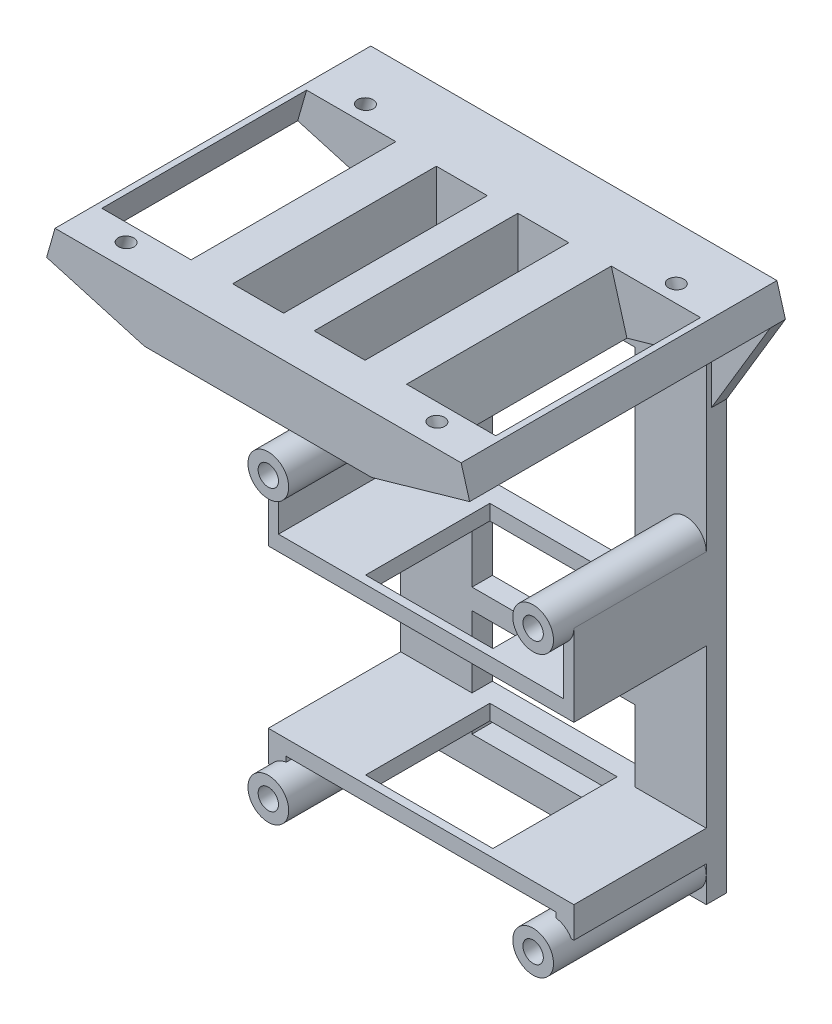
SolidWorks part; units mm, degrees
ref_plane "前基準面" through (0, 0, 0) normal (0, 0, 1) x (1, 0, 0)
ref_plane "上基準面" through (0, 0, 0) normal (0, 1, 0) x (1, 0, 0)
ref_plane "右基準面" through (0, 0, 0) normal (1, 0, 0) x (0, 0, -1)
sketch "草圖1" plane through (0, 0, 0) normal (0, 0, 1) x (1, 0, 0)
  line L0 (-15, 0) -> (15, 0)
  line L1 (-15, 0) -> (-17.2274, 0)
  line L2 (20.7676, -12.3462) -> (15, -14)
  line L3 (15, -14) -> (15, -64)
  line L4 (15, -64) -> (-15, -64)
  line L5 (-15, -64) -> (-15, -14)
  line L6 (-15, -14) -> (-20.7676, -12.3462)
  line L7 (-17.2274, 0) -> (-20.7676, -12.3462)
  line L8 (0, 15.1551) -> (0, -26.7536) construction
  line L9 (15, 0) -> (17.1989, 0)
  line L10 (17.1989, 0) -> (20.7676, -12.3462)
  dimension "D7" = 74
  dimension "D8" = 6
  dimension "D9" = 14
  dimension "D1" = 30
  dimension "D2" = 15
  dimension "D3" = 30
  dimension "D4" = 15
  dimension "D5" = 50
  dimension "D6" = 148
  dimension "D11" = 90
extrude "填料-伸長1" add sketch "草圖1" along normal blind 2
sketch "草圖2" plane through (0, 0, 2) normal (0, 0, 1) x (1, 0, 0)
  line L0 (0, 35.4377) -> (0, -39.094) construction
  line L1 (-19.9407, -9.4624) -> (19.9345, -9.4642)
  line L2 (-20.7676, -12.3462) -> (-11.155, -15.1025)
  line L3 (-11.155, -15.1025) -> (11.155, -15.1025)
  line L4 (11.155, -15.1025) -> (20.7676, -12.3462)
  line L5 (15, -14) -> (20.7676, -12.3462) construction
  line L6 (-20.7676, -12.3462) -> (-15, -14) construction
  line L7 (-20.7676, -12.3462) -> (-19.9407, -9.4624)
  line L8 (-17.2274, 0) -> (-20.7676, -12.3462) construction
  line L12 (20.7676, -12.3462) -> (17.1989, 0) construction
  line L13 (19.9345, -9.4642) -> (20.7676, -12.3462)
  dimension "D1" = 10
  dimension "D2" = 3
  dimension "D3" = 3
extrude "填料-伸長2" add sketch "草圖2" along normal blind 29 and the other way blind 2
sketch "草圖3" plane through (3.5569, -17.2812, 0) normal (-0.2756, 0.9613, 0) x (0.9613, 0.2756, 0)
  line L0 (7.9042, -31) -> (17.9042, -31) construction
  line L5 (17.8978, -6.9) -> (8.8978, -6.9)
  line L6 (17.8978, -6.9) -> (17.8978, -27)
  line L7 (17.8978, -27) -> (8.8978, -27)
  line L8 (8.8978, -6.9) -> (8.8978, -27)
  circle A2 centre (13.3978, -5.2) radius 0.75
  circle A3 centre (13.3978, -28.7) radius 0.75
  dimension "D7" = 1.5
  dimension "D2" = 20.1
  dimension "D3" = 9
  dimension "D4" = 23.5
  dimension "D5" = 1.7
  dimension "D6" = 4
  dimension "D11" = 4.5
extrude "除料-伸長5" cut sketch "草圖3" along normal up to next
sketch "草圖12" plane through (-4.8491, -16.9107, 0) normal (-0.2756, -0.9613, 0) x (0.9613, -0.2756, 0)
  line L0 (-16.56, 31) -> (-16.56, 0) construction
  line L1 (-16.56, 27) -> (-7.56, 27)
  line L2 (-16.56, 27) -> (-16.56, 6.9)
  line L3 (-16.56, 6.9) -> (-7.56, 6.9)
  line L4 (-7.56, 27) -> (-7.56, 6.9)
  line L5 (-16.56, 31) -> (-6.56, 31) construction
  circle A0 centre (-12.06, 28.7) radius 0.75
  circle A1 centre (-12.06, 5.2) radius 0.75
  dimension "D7" = 1.5
  dimension "D8" = 1.5
  dimension "D1" = 9
  dimension "D2" = 20.1
  dimension "D3" = 4
  dimension "D4" = 23.5
  dimension "D5" = 1.7
  dimension "D6" = 4.5
extrude "除料-伸長7" cut sketch "草圖12" against normal up to next
sketch "草圖13" plane through (0, 0, 2) normal (0, 0, 1) x (1, 0, 0)
  line L1 (-15, -64) -> (15, -64) construction
  line L2 (-11.155, -15.1025) -> (11.155, -15.1025) construction
  line L3 (-8, -20.1025) -> (8, -20.1025)
  line L4 (-8, -20.1025) -> (-8, -61)
  line L5 (-8, -61) -> (8, -61)
  line L6 (8, -20.1025) -> (8, -61)
  line L7 (-8, -20.1025) -> (8, -61) construction
  line L8 (-8, -61) -> (8, -20.1025) construction
  circle A0 centre (-13, -34) radius 1
  circle A1 centre (13, -34) radius 1
  circle A2 centre (-13, -61.5) radius 1
  circle A3 centre (13, -61.5) radius 1
  point P11 (0, -40.5513)
  dimension "D4" = 2
  dimension "D5" = 2
  dimension "D6" = 2
  dimension "D7" = 2
  dimension "D1" = 26
  dimension "D2" = 27.5
  dimension "D3" = 2.5
  dimension "D8" = 13
  dimension "D9" = 16
  dimension "D10" = 3
  dimension "D11" = 5
extrude "除料-伸長8" cut sketch "草圖13" against normal up to next
sketch "草圖15" plane through (0, 0, 2) normal (0, 0, 1) x (1, 0, 0)
  circle A0 centre (-13, -34) radius 1
  circle A1 centre (-13, -34) radius 2
  circle A2 centre (13, -34) radius 1
  circle A3 centre (13, -34) radius 2
  circle A4 centre (13, -61.5) radius 1
  circle A5 centre (13, -61.5) radius 2
  circle A6 centre (-13, -61.5) radius 1
  circle A7 centre (-13, -61.5) radius 2
extrude "填料-伸長9" add sketch "草圖15" along normal blind 15
sketch "草圖16" plane through (0, -15.1025, 0) normal (0, -1, 0) x (1, 0, 0)
  line L1 (-1.5, 27) -> (-6.5, 27)
  line L2 (-1.5, 27) -> (-1.5, 7)
  line L3 (-1.5, 7) -> (-6.5, 7)
  line L4 (-6.5, 27) -> (-6.5, 7)
  line L6 (1.5, 27) -> (6.5, 27)
  line L7 (1.5, 27) -> (1.5, 7)
  line L8 (1.5, 7) -> (6.5, 7)
  line L9 (6.5, 27) -> (6.5, 7)
  dimension "D1" = 5
  dimension "D2" = 5
  dimension "D3" = 20
  dimension "D4" = 20
  dimension "D5" = 7
  dimension "D6" = 7
  dimension "D7" = 3
  dimension "D8" = 1.5
extrude "除料-伸長9" cut sketch "草圖16" against normal up to next
sketch "草圖17" plane through (0, 0, 31) normal (0, 0, 1) x (1, 0, 0)
  line L0 (-19.9407, -9.4624) -> (-20.7676, -12.3462)
  line L1 (-20.7676, -12.3462) -> (-20.2131, -12.5052)
  line L2 (-19.9407, -9.4624) -> (19.9345, -9.4642) construction
  line L3 (-20.7676, -12.3462) -> (-11.155, -15.1025) construction
  line L4 (19.3345, -9.4641) -> (19.9345, -9.4642)
  line L5 (-20.2131, -12.5052) -> (-19.3407, -9.4624)
  line L7 (19.9345, -9.4642) -> (20.7676, -12.3462)
  line L8 (20.7676, -12.3462) -> (20.207, -12.5069)
  line L9 (11.155, -15.1025) -> (20.7676, -12.3462) construction
  line L10 (20.207, -12.5069) -> (19.3345, -9.4641)
  line L12 (19.9345, -9.4642) -> (-19.9407, -9.4624) construction
  line L13 (-19.9407, -9.4624) -> (-19.3407, -9.4624)
  dimension "D1" = 0.6
  dimension "D2" = 0.6
extrude "填料-伸長10" add sketch "草圖17" against normal up to surface (24.1 mm away) up to face at (15.8444, -11.5261, 6.9)
sketch "草圖18" plane through (0, 0, 0) normal (0, 0, -1) x (-1, 0, 0)
  line L0 (-20.7676, -12.3462) -> (-15, -22)
  line L1 (-15, -14) -> (-15, -22)
  line L2 (-15, -64) -> (-15, -14) construction
  line L3 (-20.7676, -12.3462) -> (-15, -14)
  line L4 (20.7676, -12.3462) -> (15, -14)
  line L5 (15, -14) -> (15, -22)
  line L6 (15, -14) -> (15, -64) construction
  line L7 (15, -22) -> (20.7676, -12.3462)
  dimension "D1" = 8
extrude "填料-伸長11" add sketch "草圖18" against normal blind 1.5
sketch "草圖19" plane through (0, 0, 2) normal (0, 0, 1) x (1, 0, 0)
  line L0 (-19.9407, -9.4624) -> (19.9345, -9.4642)
  line L1 (19.9345, -9.4642) -> (19.9345, 2.3415)
  line L2 (19.9345, 2.3415) -> (-19.9407, 2.3415)
  line L3 (-19.9407, 2.3415) -> (-19.9407, -9.4624)
extrude "除料-伸長10" cut sketch "草圖19" against normal up to next
sketch "草圖20" plane through (0, 0, 0) normal (0, 0, -1) x (-1, 0, 0)
  line L0 (-15, -64) -> (-15, -22) construction
  line L1 (-15, -57.5) -> (15, -57.5)
  line L2 (-15, -57.5) -> (-15, -59)
  line L3 (-15, -59) -> (15, -59)
  line L4 (15, -57.5) -> (15, -59)
  line L5 (15, -22) -> (15, -64) construction
  line L6 (15, -64) -> (-15, -64) construction
  line L7 (-15, -40.5) -> (15, -40.5)
  line L8 (-15, -40.5) -> (-15, -42)
  line L9 (-15, -42) -> (15, -42)
  line L10 (15, -40.5) -> (15, -42)
  dimension "D1" = 15.5
  dimension "D2" = 1.5
  dimension "D3" = 1.5
  dimension "D4" = 5
extrude "填料-伸長12" add sketch "草圖20" against normal blind 15
sketch "草圖21" plane through (0, 0, 0) normal (0, 0, -1) x (-1, 0, 0)
  line L0 (-8, -57.5) -> (-8, -42) construction
  line L1 (-8, -48.5) -> (8, -48.5)
  line L2 (-8, -48.5) -> (-8, -50.5)
  line L3 (-8, -50.5) -> (8, -50.5)
  line L4 (8, -48.5) -> (8, -50.5)
  line L5 (8, -42) -> (8, -57.5) construction
  line L6 (-8, -42) -> (8, -42) construction
  dimension "D1" = 2
  dimension "D2" = 6.5
extrude "填料-伸長13" add sketch "草圖21" against normal up to surface (2 mm away) up to face at (-11.5, -49.75, 2)
sketch "草圖22" plane through (0, 0, 15) normal (0, 0, 1) x (1, 0, 0)
  line L1 (15, -42) -> (14, -42)
  line L2 (15, -42) -> (15, -34)
  line L3 (15, -34) -> (14, -34)
  line L4 (14, -42) -> (14, -34)
  line L5 (-15, -42) -> (-14, -42)
  line L6 (-15, -42) -> (-15, -34)
  line L7 (-15, -34) -> (-14, -34)
  line L8 (-14, -42) -> (-14, -34)
  line L9 (15, -59) -> (13.2425, -59)
  line L10 (15, -59) -> (15, -60.5299)
  line L11 (15, -60.5299) -> (13.2425, -60.5299)
  line L12 (13.2425, -59) -> (13.2425, -60.5299)
  line L13 (-15, -59) -> (-13.2425, -59)
  line L14 (-15, -59) -> (-15, -60.5299)
  line L15 (-15, -60.5299) -> (-13.2425, -60.5299)
  line L16 (-13.2425, -59) -> (-13.2425, -60.5299)
  circle A0 centre (13, -34) radius 1 construction
  circle A1 centre (-13, -34) radius 1 construction
  circle A2 centre (13, -61.5) radius 1 construction
  circle A3 centre (-13, -61.5) radius 1 construction
extrude "填料-伸長14" add sketch "草圖22" against normal up to surface (13 mm away) up to face at (0, -49.6667, 2)
sketch "草圖23" plane through (0, -59, 0) normal (0, -1, 0) x (1, 0, 0)
  line L0 (13.2425, 2) -> (8, 2) construction
  line L1 (-6.25, 14.2) -> (6.25, 14.2)
  line L2 (-6.25, 14.2) -> (-6.25, 2)
  line L3 (-6.25, 2) -> (6.25, 2)
  line L4 (6.25, 14.2) -> (6.25, 2)
  line L5 (-6.25, 14.2) -> (6.25, 2) construction
  line L6 (-6.25, 2) -> (6.25, 14.2) construction
  point P0 (0, 8.1)
  dimension "D1" = 12.5
  dimension "D2" = 12.2
extrude "除料-伸長11" cut sketch "草圖23" against normal up to surface (18.5 mm away) up to face at (0, -40.5, 4.75)
